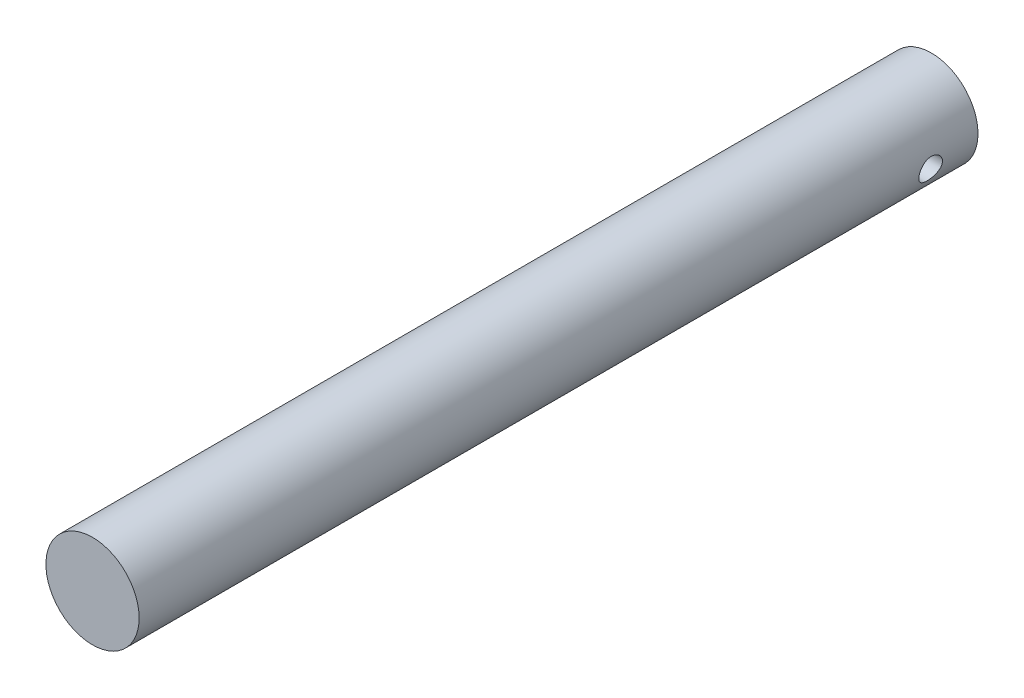
SolidWorks part; units mm, degrees
ref_plane "Front Plane" through (0, 0, 0) normal (0, 0, 1) x (1, 0, 0)
ref_plane "Top Plane" through (0, 0, 0) normal (0, 1, 0) x (1, 0, 0)
ref_plane "Right Plane" through (0, 0, 0) normal (1, 0, 0) x (0, 0, -1)
sketch "Sketch1" plane through (0, 0, 0) normal (0, 0, 1) x (1, 0, 0)
  circle A0 centre (-5.1467, 5.6335) radius 6.35
  dimension "D1" = 12.7
extrude "Boss-Extrude1" add sketch "Sketch1" along normal blind 114.3
ref_plane "Plane2" through (1.2033, 0, 0) normal (1, 0, 0) x (0, 0, -1)
sketch "Sketch2" plane through (1.2033, 0, 0) normal (1, 0, 0) x (0, 0, -1)
  line L0 (0, -0.7165) -> (0, 11.9835) construction
  circle A0 centre (-6.35, 4.533) radius 1.5875
  dimension "D1" = 3.175
  dimension "D2" = 6.35
extrude "Cut-Extrude1" cut sketch "Sketch2" against normal blind 23.114
